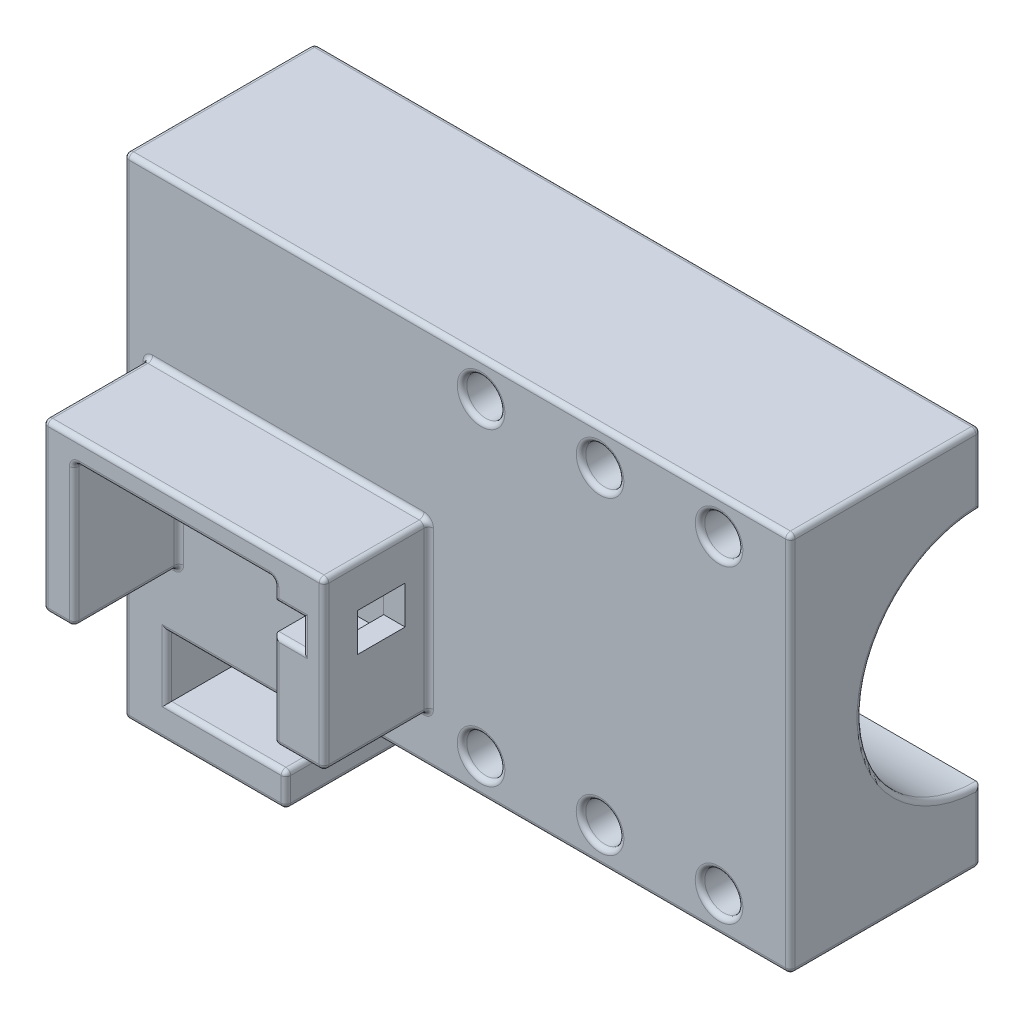
SolidWorks part; units mm, degrees
material "PLA"
ref_plane "Alzado" through (0, 0, 0) normal (0, 0, 1) x (1, 0, 0)
ref_plane "Planta" through (0, 0, 0) normal (0, 1, 0) x (1, 0, 0)
ref_plane "Vista lateral" through (0, 0, 0) normal (1, 0, 0) x (0, 0, -1)
sketch "Sketch5" plane through (0, 0, 0) normal (0, 1, 0) x (1, 0, 0)
  line L0 (40, 0) -> (40, 40) construction
  line L1 (0, 0) -> (80, 0)
  line L2 (0, 0) -> (0, 40)
  line L3 (0, 40) -> (80, 40)
  line L4 (80, 0) -> (80, 40)
  dimension "D1" = 40
  dimension "D2" = 80
extrude "Boss-Extrude2" add sketch "Sketch5" along normal blind 80
sketch "Sketch16" plane through (0, 0, 0) normal (-1, 0, 0) x (0, 0, 1)
  line L1 (-40, 80) -> (0, 80)
  line L2 (-40, 80) -> (-40, 0)
  line L3 (-40, 0) -> (0, 0)
  line L4 (0, 80) -> (0, 0)
extrude "Boss-Extrude3" add sketch "Sketch16" along normal blind 60
sketch "Sketch9" plane through (80, 0, 0) normal (1, 0, 0) x (0, 0, -1)
  line L0 (40, 40) -> (0, 40) construction
  line L1 (40, 80) -> (40, 0) construction
  line L2 (0, 80) -> (0, 0) construction
  circle A0 centre (40, 40) radius 25
  dimension "D1" = 50
extrude "Cut-Extrude5" cut sketch "Sketch9" against normal through all
sketch "Sketch18" plane through (0, 0, 0) normal (0, 0, 1) x (1, 0, 0)
  line L0 (-60, 0) -> (80, 0) construction
  line L1 (-55, 0) -> (0, 0)
  line L2 (-55, 0) -> (-55, 45)
  line L3 (-55, 45) -> (0, 45)
  line L4 (0, 0) -> (0, 45)
  line L5 (-60, 0) -> (-60, 80) construction
  line L6 (-48.5, 0) -> (-6.5, 0)
  line L7 (-48.5, 0) -> (-48.5, 40)
  line L8 (-48.5, 40) -> (-6.5, 40)
  line L9 (-6.5, 0) -> (-6.5, 40)
  line L10 (-48.5, 10) -> (-55, 10)
  line L11 (-6.5, 10) -> (0, 10)
  dimension "D1" = 55
  dimension "D2" = 42
  dimension "D3" = 6.5
  dimension "D4" = 5
  dimension "D5" = 40
  dimension "D6" = 45
  dimension "D7" = 30
extrude "Boss-Extrude5" add sketch "Sketch18" along normal blind 22 contours L9 L11 L4 L3 L2 L10 L7 L8
sketch "Sketch19" plane through (0, 0, 0) normal (0, -1, 0) x (1, 0, 0)
  line L0 (-6.5, 5) -> (-0.5, 5)
  line L1 (-6.5, 22) -> (-6.5, 0) construction
  line L2 (-0.5, 5) -> (-0.5, 15)
  line L3 (-0.5, 15) -> (-6.5, 15)
  line L4 (-6.5, 22) -> (-6.5, 0) construction
  line L5 (-6.5, 15) -> (-6.5, 5)
  dimension "D1" = 5
  dimension "D2" = 10
  dimension "D3" = 6
extrude "Cut-Extrude12" cut sketch "Sketch19" against normal up to surface (40 mm away) up to face at (-27.5, 40, 11)
sketch "Sketch21" plane through (0, 0, 0) normal (0, 0, 1) x (1, 0, 0)
  line L1 (0, 45) -> (4, 45)
  line L2 (0, 45) -> (0, 10)
  line L3 (0, 10) -> (4, 10)
  line L4 (4, 45) -> (4, 10)
  dimension "D1" = 4
  dimension "D2" = 35
extrude "Boss-Extrude6" add sketch "Sketch21" along normal up to surface (22 mm away) up to face at (-27.5, 26.25, 22)
sketch "Sketch22" plane through (0, 10, 0) normal (0, -1, 0) x (-1, 0, 0)
  line L1 (6.5, -15) -> (0.5, -15)
  line L2 (6.5, -15) -> (6.5, -5)
  line L3 (6.5, -5) -> (0.5, -5)
  line L4 (0.5, -15) -> (0.5, -5)
extrude "Boss-Extrude7" add sketch "Sketch22" against normal blind 15
sketch "Sketch23" plane through (-0.5, 0, 0) normal (-1, 0, 0) x (0, 0, 1)
  line L0 (22, 45) -> (0, 45) construction
  line L1 (4.9512, 36) -> (14.9512, 36)
  line L2 (4.9512, 36) -> (4.9512, 28)
  line L3 (4.9512, 28) -> (14.9512, 28)
  line L4 (14.9512, 36) -> (14.9512, 28)
  dimension "D1" = 9
  dimension "D2" = 8
  dimension "D3" = 10
extrude "Cut-Extrude13" cut sketch "Sketch23" against normal up to surface (4.5 mm away) up to face at (4, 27.5, 11)
sketch "Sketch24" plane through (0, 10, 0) normal (0, -1, 0) x (-1, 0, 0)
  line L1 (51.5, -22) -> (51.5, 0) construction
  line L4 (48.5, -22) -> (55, -22) construction
  line L5 (48.5, 0) -> (55, 0) construction
  line L6 (3.5, -22) -> (3.5, 0) construction
  line L7 (6.5, -22) -> (-4, -22) construction
  line L8 (60, 0) -> (-80, 0) construction
  circle A0 centre (51.5, -5) radius 0.75
  circle A1 centre (51.5, -15) radius 0.75
  circle A2 centre (3.5, -15) radius 0.75
  circle A3 centre (3.5, -5) radius 0.75
  dimension "D3" = 5
  dimension "D7" = 1.5
  dimension "D8" = 1.5
  dimension "D9" = 1.5
  dimension "D10" = 1.5
  dimension "D1" = 3
  dimension "D2" = 3
  dimension "D4" = 10
  dimension "D5" = 5
  dimension "D6" = 10
extrude "Cut-Extrude14" cut sketch "Sketch24" against normal blind 12
sketch "Sketch25" plane through (0, 0, 0) normal (0, -1, 0) x (1, 0, 0)
  line L0 (-60, -40) -> (80, -40) construction
  line L1 (-52, -40) -> (-34, -40)
  line L2 (-52, -40) -> (-52, 0)
  line L3 (-52, 0) -> (-34, 0)
  line L4 (-34, -40) -> (-34, 0)
  line L5 (-60, 0) -> (80, 0) construction
  line L6 (-60, -40) -> (-60, 0) construction
  dimension "D1" = 8
  dimension "D2" = 18
extrude "Boss-Extrude8" add sketch "Sketch25" along normal blind 3
sketch "Sketch26" plane through (0, 0, 0) normal (0, 0, 1) x (1, 0, 0)
  line L0 (-60, 0) -> (-60, -23)
  line L1 (-60, -23) -> (-26, -23)
  line L2 (-26, -23) -> (-26, 0)
  line L3 (-34, 0) -> (80, 0) construction
  line L4 (-26, 0) -> (-34, 0)
  line L5 (-34, 0) -> (-34, -3)
  line L6 (-34, -3) -> (-52, -3)
  line L7 (-52, -3) -> (-52, 0)
  line L8 (-52, 0) -> (-60, 0)
  line L9 (-52, -3) -> (-52, -17)
  line L10 (-52, -17) -> (-34, -17)
  line L11 (-34, -17) -> (-34, -3)
  line M13 (-60, 0) -> (-52, 0)
  line M14 (-52, 0) -> (-52, -3)
  line M16 (-34, -3) -> (-34, 0)
  line M17 (-34, 0) -> (80, 0)
  dimension "D1" = 8
  dimension "D2" = 14
  dimension "D3" = 20
extrude "Boss-Extrude9" add sketch "Sketch26" against normal through all contours L11 L10 L9 L0 L1 L2 M14 M13 M17 M16
sketch "Sketch27" plane through (0, 0, 0) normal (0, 0, 1) x (1, 0, 0)
  line L0 (-26, -23) -> (-26, 0) construction
  line L1 (-34, -17) -> (-26, -17)
  line L2 (-34, -17) -> (-34, -3)
  line L3 (-34, -3) -> (-26, -3)
  line L4 (-26, -17) -> (-26, -3)
extrude "Cut-Extrude15" cut sketch "Sketch27" against normal blind 12.5
sketch "Sketch28" plane through (0, 0, 0) normal (0, 0, 1) x (1, 0, 0)
  line L0 (-26, -17) -> (-26, -3) construction
  line L1 (-52, -17) -> (-26, -17)
  line L2 (-52, -17) -> (-52, -16)
  line L3 (-52, -16) -> (-26, -16)
  line L4 (-26, -17) -> (-26, -16)
  dimension "D1" = 1
extrude "Boss-Extrude10" add sketch "Sketch28" against normal through all
sketch "Sketch29" plane through (0, 0, 0) normal (0, 0, 1) x (1, 0, 0)
  line L0 (-26, -3) -> (-52, -3) construction
  line L1 (-52, -16) -> (-51, -16)
  line L2 (-52, -16) -> (-52, -3)
  line L3 (-52, -3) -> (-51, -3)
  line L4 (-51, -16) -> (-51, -3)
  dimension "D1" = 1
extrude "Boss-Extrude11" add sketch "Sketch29" against normal through all
sketch "Sketch30" plane through (0, 0, 0) normal (0, 0, 1) x (1, 0, 0)
  line L0 (80, 7.5) -> (9.9227, 7.5) construction
  line L1 (80, 80) -> (80, 0) construction
  line L2 (9.9227, 7.5) -> (9.9227, 72.5) construction
  line L3 (9.9227, 72.5) -> (80, 72.5) construction
  line L4 (-60, 80) -> (80, 80) construction
  line L6 (-26, 0) -> (80, 0) construction
  circle A0 centre (15, 72.5) radius 2.375
  circle A1 centre (40, 72.5) radius 2.375
  circle A2 centre (65, 72.5) radius 2.375
  circle A3 centre (15, 7.5) radius 2.375
  circle A4 centre (40, 7.5) radius 2.375
  circle A5 centre (65, 7.5) radius 2.375
  point P10 (65, 72.5)
  point P11 (40, 72.5)
  point P12 (15, 72.5)
  point P13 (15, 7.5)
  point P14 (40, 7.5)
  point P15 (65, 7.5)
  dimension "D9" = 4.75
  dimension "D10" = 4.75
  dimension "D11" = 4.75
  dimension "D12" = 4.75
  dimension "D13" = 4.75
  dimension "D14" = 4.75
  dimension "D1" = 7.5
  dimension "D2" = 7.5
  dimension "D3" = 15
  dimension "D4" = 25
  dimension "D5" = 25
  dimension "D6" = 15
  dimension "D7" = 25
  dimension "D8" = 25
extrude "Cut-Extrude16" cut sketch "Sketch30" against normal through all
sketch "Sketch33" plane through (0, 0, 0) normal (0, 0, 1) x (1, 0, 0)
  circle A0 centre (15, 7.5) radius 4
  circle A1 centre (40, 7.5) radius 4
  circle A2 centre (65, 7.5) radius 4
  circle A3 centre (65, 72.5) radius 4
  circle A4 centre (40, 72.5) radius 4
  circle A5 centre (15, 72.5) radius 4
  dimension "D1" = 8
  dimension "D2" = 8
  dimension "D3" = 8
  dimension "D4" = 8
  dimension "D5" = 8
  dimension "D6" = 8
extrude "Cut-Extrude17" cut sketch "Sketch33" against normal blind 25
sketch "Sketch34" plane through (0, 0, 22) normal (0, 0, 1) x (1, 0, 0)
  line L0 (-6.5, 10) -> (-6.5, 40) construction
  line L1 (-6.5, 36) -> (-0.5, 36)
  line L2 (-6.5, 36) -> (-6.5, 30)
  line L3 (-6.5, 30) -> (-0.5, 30)
  line L4 (-0.5, 36) -> (-0.5, 30)
  line L5 (-6.5, 10) -> (4, 10) construction
  dimension "D1" = 20
  dimension "D2" = 6
  dimension "D3" = 6
extrude "Cut-Extrude18" cut sketch "Sketch34" against normal blind 10
fillet "Fillet1" radius 1 73 edges at (80, 80, -20) (-3.5, 10, 4.25) (-3.5, 10, 14.25) (-51.5, 10, 14.25) (-51.5, 10, 4.25) (10, 80, -40) (-34, -3, -26.25) (-38.5, -3, 0) (27, 0, -40) (27, 0, 0) (-26, -11.5, -40) (-26, 0, -20) (-43, -23, -40) (-26, -23, -20) (-60, -23, -20) (-43, -23, 0) (-26, -19.5, 0) (-60, 72.5, -40) (-60, 28.5, 0) (-60, 80, -20) (-26, -1.5, 0) (-26, -3, -6.25) (-26, -9.5, -12.5) (-26, -16, -6.25) (-38.5, -16, 0) (-51, -9.5, 0) (-60, -4, -40) (80, 7.5, -40) (19, 72.5, 0) (44, 72.5, 0) (69, 72.5, 0) (69, 7.5, 0) (44, 7.5, 0) (19, 7.5, 0) (-60, 40, -15) (80, 40, -15) (-6.5, 38, 22) (-3.5, 30, 22) (-0.5, 33, 22) (-3.5, 36, 22) (-6.5, 20, 22) (-6.5, 40, 18.5) (-1.25, 10, 0) (-6.5, 10, 11) (-25.5, 45, 22) (-55, 27.5, 22) (-55, 45, 11) (-51.75, 10, 22) (-55, 10, 11) (-48.5, 25, 0) (-48.5, 10, 11) (-27.5, 40, 0) (-48.5, 40, 11) (-1.25, 10, 22) (-48.5, 25, 22) (-27.5, 40, 22) (-6.5, 25, 0) (-51.75, 10, 0) (-55, 27.5, 0) (-25.5, 45, 0) (10, 80, 0) (-6.5, 40, 2.5) (80, 0, -20) (-3.5, 40, 5) (-0.5, 40, 10) (-3.5, 40, 15) (4, 10, 11) (4, 27.5, 0) (4, 45, 11) (4, 27.5, 22) (80, 72.5, -40) (80, 40, 0) (-0.5, 25, 10)
